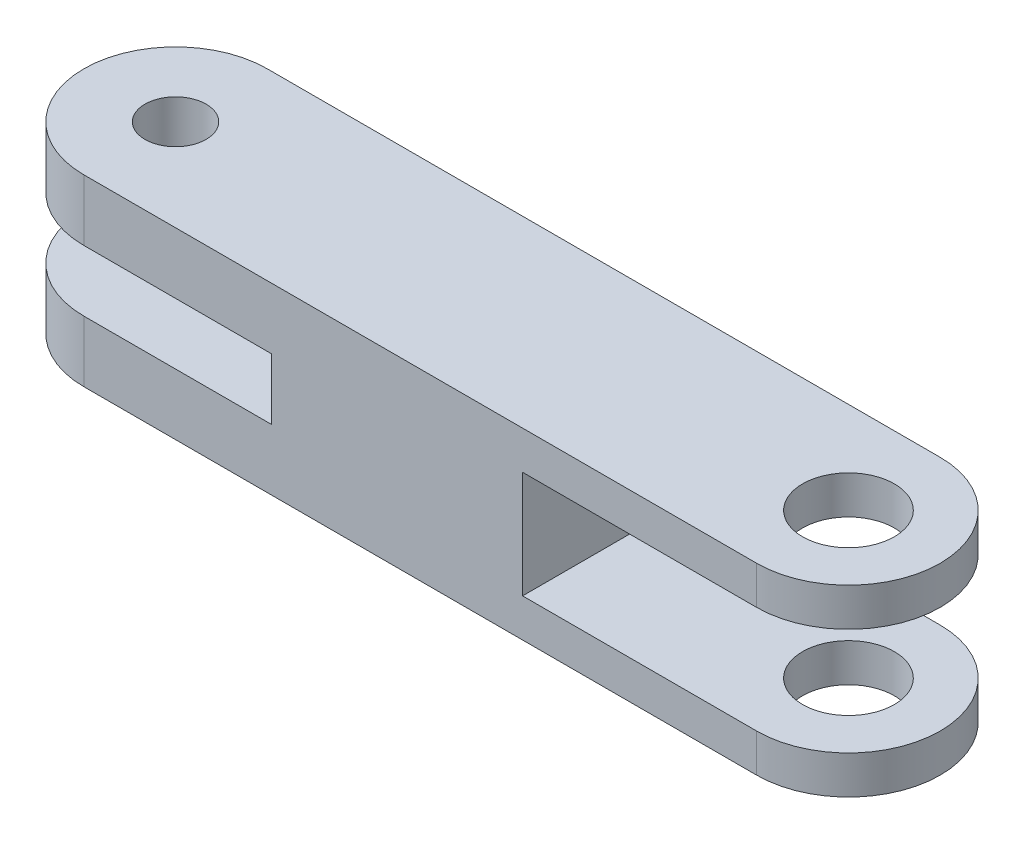
SolidWorks part; units mm, degrees
ref_plane "前视基准面" through (0, 0, 0) normal (0, 0, 1) x (1, 0, 0)
ref_plane "上视基准面" through (0, 0, 0) normal (0, 1, 0) x (1, 0, 0)
ref_plane "右视基准面" through (0, 0, 0) normal (1, 0, 0) x (0, 0, -1)
other "Configuration Table"
sketch "草图1" plane through (0, 0, 0) normal (0, 1, 0) x (1, 0, 0)
  line L0 (0, 0) -> (1, 0) construction
  line L1 (20.5, 0) -> (22, 0) construction
  line L2 (0, 3) -> (22, 3)
  line L3 (0, -3) -> (22, -3)
  arc A0 (0, 3) -> (0, -3) centre (0, 0) ccw
  arc A1 (22, -3) -> (22, 3) centre (22, 0) ccw
  circle A2 centre (22, 0) radius 1.5
  circle A3 centre (0, 0) radius 1
  point P3 (20, 0)
  dimension "D2" = 3
  dimension "D3" = 3
  dimension "D4" = 2
  dimension "22" = 22
extrude "凸台-拉伸1" add sketch "草图1" along normal mid plane 6
sketch "草图6" plane through (0, 0, 0) normal (0, 1, 0) x (1, 0, 0)
  line L0 (14.3461, 7.8432) -> (14.3461, -3.762)
  line L1 (14.3461, -3.762) -> (45.8575, -3.762)
  line L2 (45.8575, -3.762) -> (45.8575, 7.8432)
  line L3 (45.8575, 7.8432) -> (14.3461, 7.8432)
extrude "切除-拉伸2" cut sketch "草图6" against normal mid plane 3.5
sketch "草图7" plane through (0, 0, 0) normal (0, 1, 0) x (1, 0, 0)
  line L0 (6.139, 5.0358) -> (6.139, -4.6141)
  line L1 (6.139, -4.6141) -> (-6.5212, -4.6141)
  line L2 (-6.5212, -4.6141) -> (-6.5212, 5.0358)
  line L3 (-6.5212, 5.0358) -> (6.139, 5.0358)
extrude "切除-拉伸3" cut sketch "草图7" against normal mid plane 2
